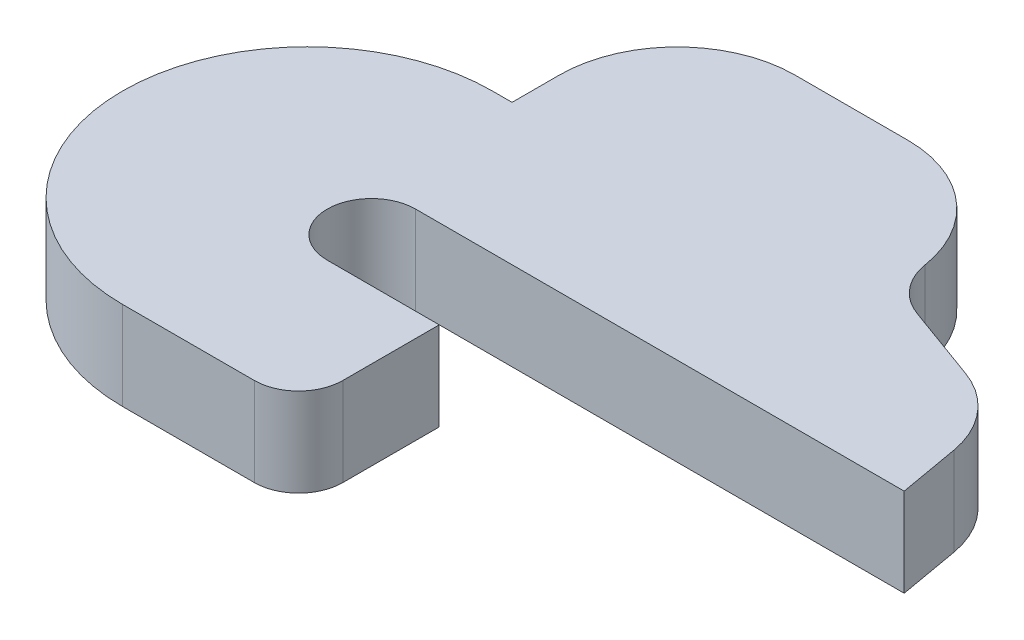
SolidWorks part; units mm, degrees
ref_plane "Front Plane" through (0, 0, 0) normal (0, 0, 1) x (1, 0, 0)
ref_plane "Top Plane" through (0, 0, 0) normal (0, 1, 0) x (1, 0, 0)
ref_plane "Right Plane" through (0, 0, 0) normal (1, 0, 0) x (0, 0, -1)
sketch "Sketch1" plane through (0, 0, 0) normal (0, 1, 0) x (1, 0, 0)
  line L0 (0, 0) -> (-3.8, 0)
  line L1 (-3.8, 3) -> (12.77, 3)
  line L2 (12.77, 3) -> (12.4088, 5.0483)
  line L5 (2.5289, 13.37) -> (-1.3, 13.37)
  line L6 (-5.3, 9.37) -> (-5.3, 7.77)
  line L7 (-5.3, 7.77) -> (-5.97, 7.77)
  line L9 (0, -3.27) -> (0, 0)
  line L10 (-5.97, -4.77) -> (-1.5, -4.77)
  line L11 (7.77, 8.4386) -> (10.351, 7.5)
  arc A0 (-3.8, 0) -> (-3.8, 3) centre (-3.8, 1.5) cw
  arc A1 (12.4088, 5.0483) -> (10.351, 7.5) centre (9.2574, 4.4927) ccw
  arc A4 (-1.3, 13.37) -> (-5.3, 9.37) centre (-1.3, 9.37) ccw
  arc A5 (-5.97, 7.77) -> (-5.97, -4.77) centre (-5.97, 1.5) ccw
  arc A8 (2.5289, 13.37) -> (6.4786, 10.0021) centre (2.5289, 9.37) cw
  arc A9 (7.77, 8.4386) -> (6.4786, 10.0021) centre (8.4535, 10.3182) cw
  arc A10 (-1.5, -4.77) -> (0, -3.27) centre (-1.5, -3.27) ccw
  point P13 (6.5012, 8.9)
  point P43 (-12.24, 1.5)
  point P44 (-5.3, 1.5)
  dimension "D1" = 5.6
  dimension "10.9" = 6.27
  dimension "D4" = 1.5
  dimension "4" = 4
  dimension "3" = 3.2
  dimension "D10" = 2
  dimension "D11" = 1.5
  dimension "D2" = 4
  dimension "D3" = 4.47
  dimension "3.65" = 4.5
  dimension "13.48" = 16.57
  dimension "80" = 80
  dimension "D8" = 6.94
  dimension "D9" = 3.8
  dimension "5" = 5
extrude "Boss-Extrude2" add sketch "Sketch1" along normal blind 3
